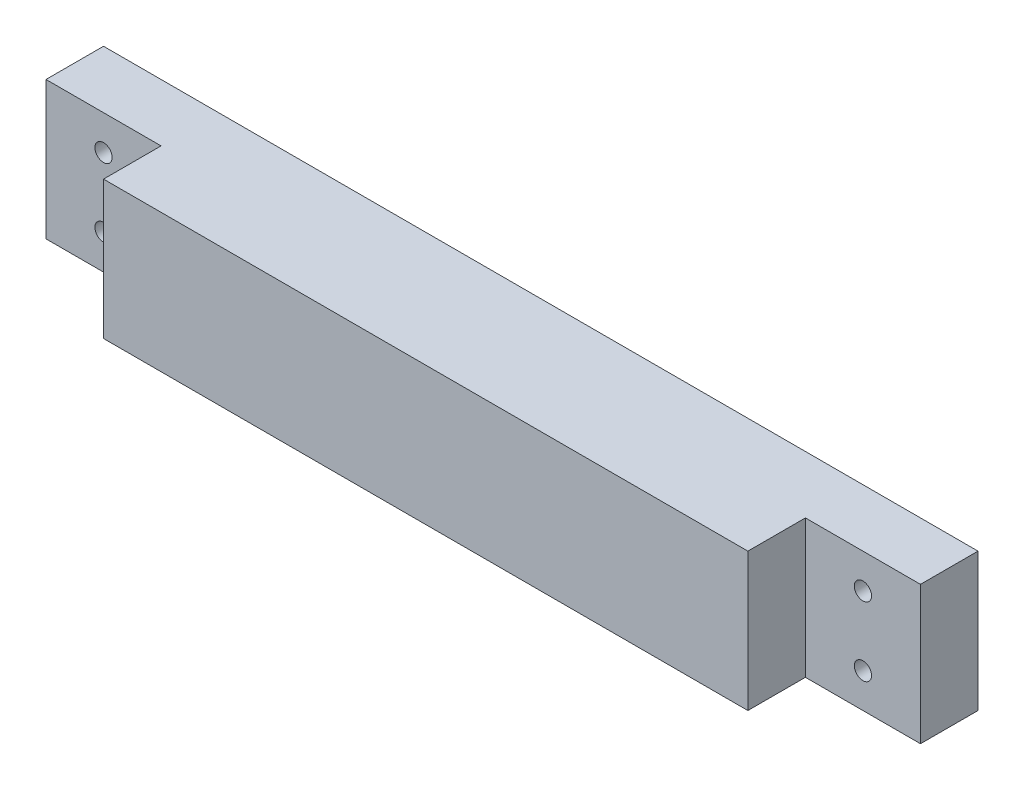
SolidWorks part; units mm, degrees
material "Pine"
ref_plane "Front Plane" through (0, 0, 0) normal (0, 0, 1) x (1, 0, 0)
ref_plane "Top Plane" through (0, 0, 0) normal (0, 1, 0) x (1, 0, 0)
ref_plane "Right Plane" through (0, 0, 0) normal (1, 0, 0) x (0, 0, -1)
sketch "Sketch1" plane through (0, 0, 0) normal (0, 0, 1) x (1, 0, 0)
  line L1 (241.3, 38.1) -> (-241.3, 38.1)
  line L2 (241.3, 38.1) -> (241.3, -38.1)
  line L3 (241.3, -38.1) -> (-241.3, -38.1)
  line L4 (-241.3, 38.1) -> (-241.3, -38.1)
  line L5 (241.3, 38.1) -> (-241.3, -38.1) construction
  line L6 (241.3, -38.1) -> (-241.3, 38.1) construction
  point P0 (0, 0)
  dimension "D1" = 482.6
  dimension "D2" = 76.2
extrude "Boss-Extrude1" add sketch "Sketch1" along normal blind 31.75
sketch "Sketch2" plane through (0, 0, 31.75) normal (0, 0, 1) x (1, 0, 0)
  line L0 (0, 0) -> (0, -38.1) construction
  line L1 (-241.3, -38.1) -> (241.3, -38.1) construction
  line L2 (241.3, 38.1) -> (-241.3, 38.1) construction
  line L3 (177.8, 38.1) -> (-177.8, 38.1)
  line L4 (177.8, 38.1) -> (177.8, -38.1)
  line L5 (177.8, -38.1) -> (-177.8, -38.1)
  line L6 (-177.8, 38.1) -> (-177.8, -38.1)
  line L7 (177.8, 38.1) -> (-177.8, -38.1) construction
  line L8 (177.8, -38.1) -> (-177.8, 38.1) construction
  point P5 (0, 0)
  dimension "D1" = 355.6
extrude "Boss-Extrude2" add sketch "Sketch2" along normal blind 31.75
sketch "Sketch3" plane through (0, 0, 31.75) normal (0, 0, 1) x (1, 0, 0)
  line L0 (-209.55, 38.1) -> (-209.55, -38.1) construction
  line L1 (-177.8, 38.1) -> (-241.3, 38.1) construction
  line L2 (-241.3, -38.1) -> (-177.8, -38.1) construction
  line L3 (-241.3, 38.1) -> (-241.3, -38.1) construction
  circle A0 centre (-209.55, 19.05) radius 4.7625
  circle A1 centre (-209.55, -19.05) radius 4.7625
  dimension "D2" = 19.05
  dimension "D3" = 19.05
  dimension "D4" = 9.525
  dimension "D1" = 31.75
extrude "Cut-Extrude1" cut sketch "Sketch3" against normal through all
mirror "Mirror1" about plane through (0, 0, 0) normal (1, 0, 0) of "Cut-Extrude1"
